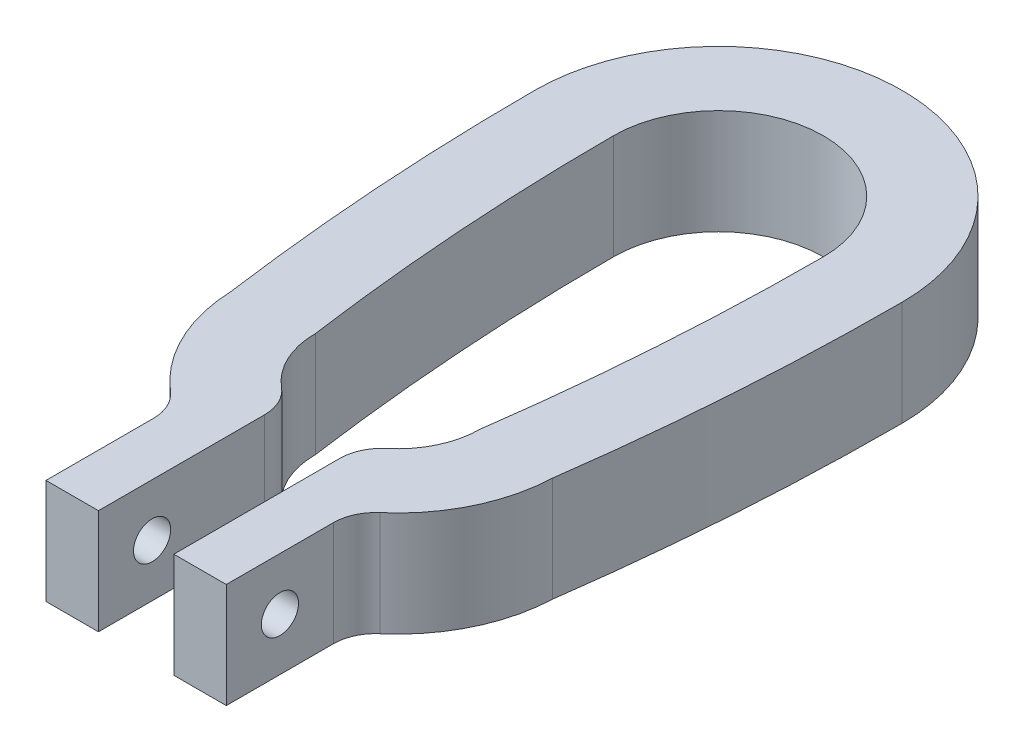
SolidWorks part; units mm, degrees
ref_plane "Front Plane" through (0, 0, 0) normal (0, 0, 1) x (1, 0, 0)
ref_plane "Top Plane" through (0, 0, 0) normal (0, 1, 0) x (1, 0, 0)
ref_plane "Right Plane" through (0, 0, 0) normal (1, 0, 0) x (0, 0, -1)
sketch "Sketch1" plane through (0, 0, 0) normal (0, 1, 0) x (1, 0, 0)
  line L1 (-12.7, 0) -> (12.7, 0) construction
  line L2 (-10, -38.8063) -> (10, -38.8063) construction
  line L4 (0, 12.7) -> (0, -25.4)
  line L5 (-4.5625, -57.7908) -> (-4.5625, -70.4908)
  line L6 (-4.5625, -70.4908) -> (-10.9125, -70.4908)
  line L7 (-10.9125, -70.4908) -> (-10.9125, -57.5052)
  line L8 (10.9125, -70.4908) -> (10.9125, -57.5052)
  line L9 (4.5625, -70.4908) -> (10.9125, -70.4908)
  line L10 (4.5625, -57.7908) -> (4.5625, -70.4908)
  line L11 (4.5625, -57.7908) -> (4.5625, -50.4007)
  line L12 (-4.5625, -57.7908) -> (-4.5625, -50.4007)
  arc A0 (12.7, 0) -> (-12.7, 0) centre (0, 0) ccw
  arc A1 (-10, -38.8063) -> (-6.3942, -46.4949) centre (0, -38.8063) ccw
  arc A2 (-12.7, 0) -> (-10, -38.8063) centre (267.5262, 0) ccw
  arc A3 (12.7, 0) -> (10, -38.8063) centre (-267.5262, 0) cw
  arc A4 (22.225, 0) -> (-22.225, 0) centre (0, 0) ccw
  arc A5 (-22.225, 0) -> (-19.51, -39.5728) centre (267.5262, 0) ccw
  arc A6 (-19.51, -39.5728) -> (-12.6906, -53.6446) centre (0, -38.8063) ccw
  arc A7 (22.225, 0) -> (19.51, -39.5728) centre (-267.5262, 0) cw
  arc A8 (6.3942, -46.4949) -> (10, -38.8063) centre (0, -38.8063) ccw
  arc A9 (-10, -38.8063) -> (10, -38.8063) centre (0, -38.8063) ccw construction
  arc A11 (-19.51, -39.5728) -> (19.51, -39.5728) centre (0, -38.8063) ccw construction
  arc A12 (12.6906, -53.6446) -> (19.51, -39.5728) centre (0, -38.8063) ccw
  arc A13 (10.9125, -57.5052) -> (12.6906, -53.6446) centre (15.9925, -57.5052) cw
  arc A14 (-10.9125, -57.5052) -> (-12.6906, -53.6446) centre (-15.9925, -57.5052) ccw
  arc A15 (4.5625, -50.4007) -> (6.3942, -46.4949) centre (9.6425, -50.4007) cw
  arc A16 (-4.5625, -50.4007) -> (-6.3942, -46.4949) centre (-9.6425, -50.4007) ccw
  point P21 (10.9125, -54.9972)
  point P34 (-10.9125, -54.9972)
  point P37 (4.5625, -47.7049)
  point P40 (-4.5625, -47.7049)
  point P41 (0, 0)
  dimension "D1" = 25.4
  dimension "D2" = 20
  dimension "D7" = 5.08
  dimension "D8" = 5.08
  dimension "D3" = 38.1
  dimension "D4" = 9.525
  dimension "D5" = 6.35
  dimension "D6" = 12.7
extrude "Boss-Extrude1" add sketch "Sketch1" along normal blind 12.7 contours A15 L11 L10 L9 L8 A13 A12 A7 A4 A5 A6 A14 L7 L6 L5 L12 A16 A1 A2 A0 A3 A8
sketch "Sketch3" plane through (-10.9125, 0, 0) normal (-1, 0, 0) x (0, 0, 1)
  line L0 (57.5052, 12.7) -> (70.4908, 0) construction
  line L1 (70.4908, 0) -> (57.5052, 0) construction
  line L2 (70.4908, 12.7) -> (70.4908, 0) construction
  circle A0 centre (63.998, 6.35) radius 2.25
extrude "Cut-Extrude1" cut sketch "Sketch3" against normal blind 1397
